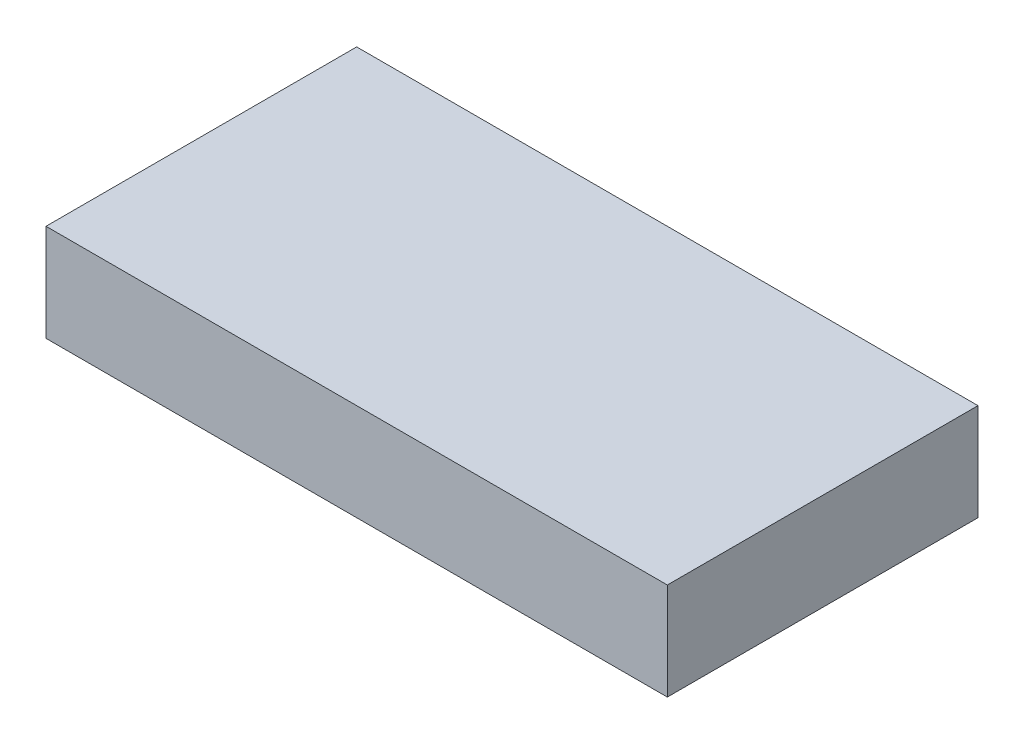
SolidWorks part; units mm, degrees
ref_plane "Front Plane" through (0, 0, 0) normal (0, 0, 1) x (1, 0, 0)
ref_plane "Top Plane" through (0, 0, 0) normal (0, 1, 0) x (1, 0, 0)
ref_plane "Right Plane" through (0, 0, 0) normal (1, 0, 0) x (0, 0, -1)
sketch "Sketch1" plane through (0, 0, 0) normal (0, 1, 0) x (1, 0, 0)
  line L1 (-17.417, 13.4317) -> (14.583, 13.4317)
  line L2 (-17.417, 13.4317) -> (-17.417, -2.5683)
  line L3 (-17.417, -2.5683) -> (14.583, -2.5683)
  line L4 (14.583, 13.4317) -> (14.583, -2.5683)
  dimension "D1" = 32
  dimension "D2" = 16
extrude "Boss-Extrude1" add sketch "Sketch1" along normal blind 5
